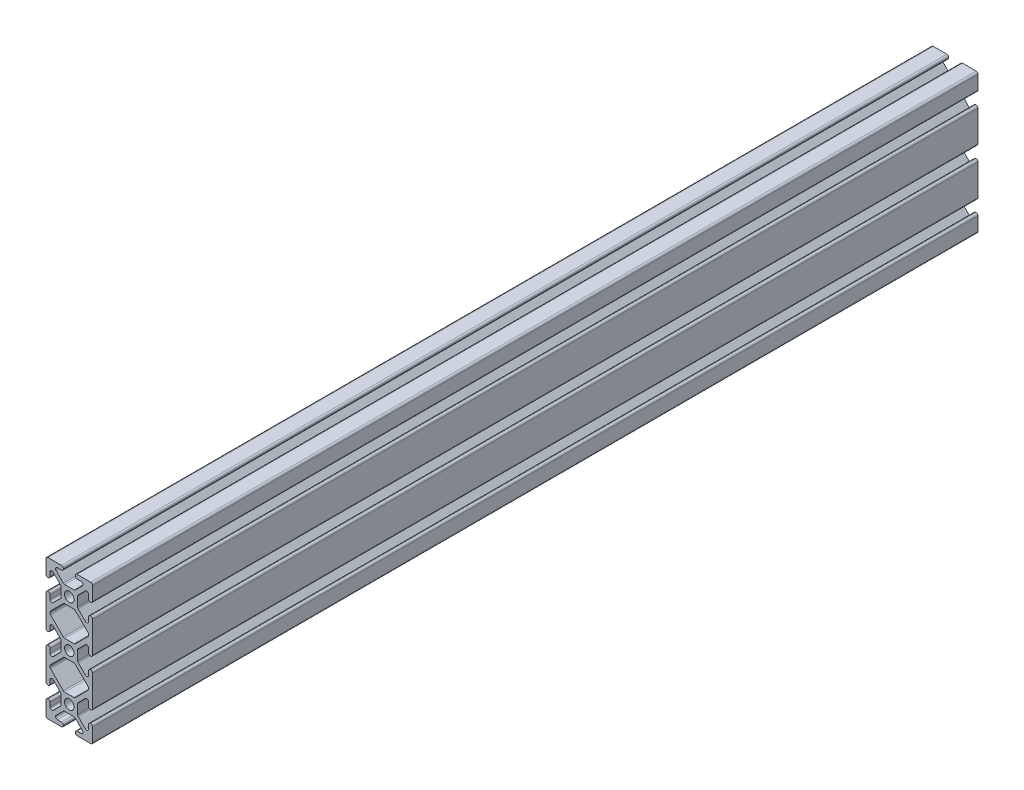
SolidWorks part; units mm, degrees
ref_plane "Front Plane" through (0, 0, 0) normal (0, 0, 1) x (1, 0, 0)
ref_plane "Top Plane" through (0, 0, 0) normal (0, 1, 0) x (1, 0, 0)
ref_plane "Right Plane" through (0, 0, 0) normal (1, 0, 0) x (0, 0, -1)
sketch "Sketch1" plane through (0, 0, 0) normal (0, 0, 1) x (1, 0, 0)
  line L0 (-12.7, 38.1) -> (-12.7, 12.7) construction
  line L1 (-12.7, -38.1) -> (12.7, -38.1) construction
  line L2 (-12.7, 12.7) -> (-12.7, -12.7) construction
  line L3 (-12.7, 38.1) -> (12.7, 38.1) construction
  line L4 (-12.7, -12.7) -> (-12.7, -38.1) construction
  line L5 (-12.7, -38.1) -> (12.7, 38.1) construction
  line L6 (-12.7, 38.1) -> (12.7, -38.1) construction
  line L7 (12.7, 38.1) -> (12.7, 12.7) construction
  line L8 (12.7, 12.7) -> (12.7, -12.7) construction
  line L9 (12.7, -12.7) -> (12.7, -38.1) construction
  line L10 (-12.7, 12.7) -> (12.7, 12.7) construction
  line L11 (-12.7, -12.7) -> (12.7, -12.7) construction
  line L12 (12.7, -12.7) -> (-12.7, -38.1) construction
  line L13 (12.7, -38.1) -> (-12.7, -12.7) construction
  line L14 (0, 38.1) -> (0, -38.1) construction
  line L15 (12.7, 12.7) -> (-12.7, 38.1) construction
  line L16 (12.7, 38.1) -> (-12.7, 12.7) construction
  line L17 (-12.7, 37.084) -> (-12.7, 29.6672)
  line L18 (-11.684, 28.6512) -> (-11.5062, 28.6512)
  line L19 (-10.4902, 29.6672) -> (-10.4902, 31.8748)
  line L20 (-8.7558, 32.5932) -> (-4.8188, 28.6562)
  line L21 (-4.5212, 27.9378) -> (-4.5212, 22.8622)
  line L22 (-4.8188, 22.1438) -> (-8.7558, 18.2068)
  line L23 (-10.4902, 18.9252) -> (-10.4902, 21.1328)
  line L24 (-11.5062, 22.1488) -> (-11.684, 22.1488)
  line L25 (-12.7, 21.1328) -> (-12.7, 4.2672)
  line L26 (-12.7, 0) -> (12.7, 0) construction
  line L27 (-12.7, -25.4) -> (12.7, -25.4) construction
  line L28 (-12.7, 25.4) -> (12.7, 25.4) construction
  line L29 (4.2672, 38.1) -> (11.684, 38.1)
  line L30 (3.2512, 36.9062) -> (3.2512, 37.084)
  line L31 (6.4748, 35.8902) -> (4.2672, 35.8902)
  line L32 (3.2562, 30.2188) -> (7.1932, 34.1558)
  line L33 (-2.5378, 29.9212) -> (2.5378, 29.9212)
  line L34 (-7.1932, 34.1558) -> (-3.2562, 30.2188)
  line L35 (-4.2672, 35.8902) -> (-6.4748, 35.8902)
  line L36 (-3.2512, 37.084) -> (-3.2512, 36.9062)
  line L37 (-11.684, 38.1) -> (-4.2672, 38.1)
  line L38 (4.5212, 2.5378) -> (4.5212, -2.5378)
  line L39 (11.5062, 22.1488) -> (11.684, 22.1488)
  line L40 (10.4902, 18.9252) -> (10.4902, 21.1328)
  line L41 (4.8188, 22.1438) -> (8.7558, 18.2068)
  line L42 (4.5212, 27.9378) -> (4.5212, 22.8622)
  line L43 (8.7558, 32.5932) -> (4.8188, 28.6562)
  line L44 (10.4902, 29.6672) -> (10.4902, 31.8748)
  line L45 (11.684, 28.6512) -> (11.5062, 28.6512)
  line L46 (12.7, 37.084) -> (12.7, 29.6672)
  line L47 (-10.4902, 12.4736) -> (-10.4902, 12.9264)
  line L48 (-10.1926, 13.6448) -> (-3.2562, 20.5812)
  line L49 (-2.5378, 20.8788) -> (2.5378, 20.8788)
  line L50 (10.4902, 12.4736) -> (10.4902, 12.9264)
  line L51 (10.1926, 13.6448) -> (3.2562, 20.5812)
  line L52 (10.1926, 11.7552) -> (3.2562, 4.8188)
  line L53 (-2.5378, 4.5212) -> (2.5378, 4.5212)
  line L54 (-10.1926, 11.7552) -> (-3.2562, 4.8188)
  line L55 (-2.5378, -4.5212) -> (2.5378, -4.5212)
  line L56 (-10.1926, -11.7552) -> (-3.2562, -4.8188)
  line L57 (10.1926, -11.7552) -> (3.2562, -4.8188)
  line L58 (10.4902, -12.4736) -> (10.4902, -12.9264)
  line L59 (10.1926, -13.6448) -> (3.2562, -20.5812)
  line L60 (-2.5378, -20.8788) -> (2.5378, -20.8788)
  line L61 (-10.1926, -13.6448) -> (-3.2562, -20.5812)
  line L62 (-10.4902, -12.4736) -> (-10.4902, -12.9264)
  line L63 (4.8188, -3.2562) -> (8.7558, -7.1932)
  line L64 (11.5062, -22.1488) -> (11.684, -22.1488)
  line L65 (10.4902, -18.9252) -> (10.4902, -21.1328)
  line L66 (4.8188, -22.1438) -> (8.7558, -18.2068)
  line L67 (4.5212, -27.9378) -> (4.5212, -22.8622)
  line L68 (8.7558, -32.5932) -> (4.8188, -28.6562)
  line L69 (10.4902, -29.6672) -> (10.4902, -31.8748)
  line L70 (11.684, -28.6512) -> (11.5062, -28.6512)
  line L71 (12.7, -37.084) -> (12.7, -29.6672)
  line L72 (3.2512, -36.9062) -> (3.2512, -37.084)
  line L73 (6.4748, -35.8902) -> (4.2672, -35.8902)
  line L74 (3.2562, -30.2188) -> (7.1932, -34.1558)
  line L75 (-2.5378, -29.9212) -> (2.5378, -29.9212)
  line L76 (-7.1932, -34.1558) -> (-3.2562, -30.2188)
  line L77 (-4.2672, -35.8902) -> (-6.4748, -35.8902)
  line L78 (-3.2512, -37.084) -> (-3.2512, -36.9062)
  line L79 (-11.684, -38.1) -> (-4.2672, -38.1)
  line L80 (4.2672, -38.1) -> (11.684, -38.1)
  line L81 (4.8188, 3.2562) -> (8.7558, 7.1932)
  line L82 (-11.5062, -22.1488) -> (-11.684, -22.1488)
  line L83 (-10.4902, -18.9252) -> (-10.4902, -21.1328)
  line L84 (-4.8188, -22.1438) -> (-8.7558, -18.2068)
  line L85 (-4.5212, -27.9378) -> (-4.5212, -22.8622)
  line L86 (-8.7558, -32.5932) -> (-4.8188, -28.6562)
  line L87 (-10.4902, -29.6672) -> (-10.4902, -31.8748)
  line L88 (-11.684, -28.6512) -> (-11.5062, -28.6512)
  line L89 (-12.7, -37.084) -> (-12.7, -29.6672)
  line L90 (-4.8188, 3.2562) -> (-8.7558, 7.1932)
  line L91 (-10.4902, 6.4748) -> (-10.4902, 4.2672)
  line L92 (-11.5062, 3.2512) -> (-11.684, 3.2512)
  line L93 (-4.5212, 2.5378) -> (-4.5212, -2.5378)
  line L94 (-12.7, -21.1328) -> (-12.7, -4.2672)
  line L95 (-4.8188, -3.2562) -> (-8.7558, -7.1932)
  line L96 (-10.4902, -6.4748) -> (-10.4902, -4.2672)
  line L97 (-11.5062, -3.2512) -> (-11.684, -3.2512)
  line L98 (10.4902, -6.4748) -> (10.4902, -4.2672)
  line L99 (10.4902, 6.4748) -> (10.4902, 4.2672)
  line L100 (11.5062, 3.2512) -> (11.684, 3.2512)
  line L101 (11.5062, -3.2512) -> (11.684, -3.2512)
  line L102 (12.7, -21.1328) -> (12.7, -4.2672)
  line L103 (12.7, 21.1328) -> (12.7, 4.2672)
  circle A0 centre (0, 25.4) radius 2.6035
  circle A1 centre (0, 0) radius 2.6035
  circle A2 centre (0, -25.4) radius 2.6035
  arc A3 (-12.7, 21.1328) -> (-11.684, 22.1488) centre (-11.684, 21.1328) cw
  arc A4 (-11.5062, 22.1488) -> (-10.4902, 21.1328) centre (-11.5062, 21.1328) cw
  arc A5 (-10.4902, 18.9252) -> (-8.7558, 18.2068) centre (-9.4742, 18.9252) ccw
  arc A6 (-4.8188, 22.1438) -> (-4.5212, 22.8622) centre (-5.5372, 22.8622) ccw
  arc A7 (-4.5212, 27.9378) -> (-4.8188, 28.6562) centre (-5.5372, 27.9378) ccw
  arc A8 (-8.7558, 32.5932) -> (-10.4902, 31.8748) centre (-9.4742, 31.8748) ccw
  arc A9 (-10.4902, 29.6672) -> (-11.5062, 28.6512) centre (-11.5062, 29.6672) cw
  arc A10 (-11.684, 28.6512) -> (-12.7, 29.6672) centre (-11.684, 29.6672) cw
  arc A11 (4.2672, 38.1) -> (3.2512, 37.084) centre (4.2672, 37.084) ccw
  arc A12 (3.2512, 36.9062) -> (4.2672, 35.8902) centre (4.2672, 36.9062) ccw
  arc A13 (6.4748, 35.8902) -> (7.1932, 34.1558) centre (6.4748, 34.8742) cw
  arc A14 (3.2562, 30.2188) -> (2.5378, 29.9212) centre (2.5378, 30.9372) cw
  arc A15 (-2.5378, 29.9212) -> (-3.2562, 30.2188) centre (-2.5378, 30.9372) cw
  arc A16 (-7.1932, 34.1558) -> (-6.4748, 35.8902) centre (-6.4748, 34.8742) cw
  arc A17 (-4.2672, 35.8902) -> (-3.2512, 36.9062) centre (-4.2672, 36.9062) ccw
  arc A18 (-3.2512, 37.084) -> (-4.2672, 38.1) centre (-4.2672, 37.084) ccw
  arc A19 (12.7, 21.1328) -> (11.684, 22.1488) centre (11.684, 21.1328) ccw
  arc A20 (11.5062, 22.1488) -> (10.4902, 21.1328) centre (11.5062, 21.1328) ccw
  arc A21 (10.4902, 18.9252) -> (8.7558, 18.2068) centre (9.4742, 18.9252) cw
  arc A22 (4.8188, 22.1438) -> (4.5212, 22.8622) centre (5.5372, 22.8622) cw
  arc A23 (4.5212, 27.9378) -> (4.8188, 28.6562) centre (5.5372, 27.9378) cw
  arc A24 (8.7558, 32.5932) -> (10.4902, 31.8748) centre (9.4742, 31.8748) cw
  arc A25 (10.4902, 29.6672) -> (11.5062, 28.6512) centre (11.5062, 29.6672) ccw
  arc A26 (11.684, 28.6512) -> (12.7, 29.6672) centre (11.684, 29.6672) ccw
  arc A27 (12.7, 37.084) -> (11.684, 38.1) centre (11.684, 37.084) ccw
  arc A28 (-11.684, 38.1) -> (-12.7, 37.084) centre (-11.684, 37.084) ccw
  arc A29 (-10.1926, 13.6448) -> (-10.4902, 12.9264) centre (-9.4742, 12.9264) ccw
  arc A30 (-2.5378, 20.8788) -> (-3.2562, 20.5812) centre (-2.5378, 19.8628) ccw
  arc A31 (10.1926, 13.6448) -> (10.4902, 12.9264) centre (9.4742, 12.9264) cw
  arc A32 (2.5378, 20.8788) -> (3.2562, 20.5812) centre (2.5378, 19.8628) cw
  arc A33 (10.1926, 11.7552) -> (10.4902, 12.4736) centre (9.4742, 12.4736) ccw
  arc A34 (2.5378, 4.5212) -> (3.2562, 4.8188) centre (2.5378, 5.5372) ccw
  arc A35 (-2.5378, 4.5212) -> (-3.2562, 4.8188) centre (-2.5378, 5.5372) cw
  arc A36 (-10.1926, 11.7552) -> (-10.4902, 12.4736) centre (-9.4742, 12.4736) cw
  arc A37 (2.5378, -4.5212) -> (3.2562, -4.8188) centre (2.5378, -5.5372) cw
  arc A38 (-2.5378, -4.5212) -> (-3.2562, -4.8188) centre (-2.5378, -5.5372) ccw
  arc A39 (10.1926, -11.7552) -> (10.4902, -12.4736) centre (9.4742, -12.4736) cw
  arc A40 (10.1926, -13.6448) -> (10.4902, -12.9264) centre (9.4742, -12.9264) ccw
  arc A41 (2.5378, -20.8788) -> (3.2562, -20.5812) centre (2.5378, -19.8628) ccw
  arc A42 (-2.5378, -20.8788) -> (-3.2562, -20.5812) centre (-2.5378, -19.8628) cw
  arc A43 (-10.1926, -13.6448) -> (-10.4902, -12.9264) centre (-9.4742, -12.9264) cw
  arc A44 (-10.1926, -11.7552) -> (-10.4902, -12.4736) centre (-9.4742, -12.4736) ccw
  arc A45 (12.7, -21.1328) -> (11.684, -22.1488) centre (11.684, -21.1328) cw
  arc A46 (11.5062, -22.1488) -> (10.4902, -21.1328) centre (11.5062, -21.1328) cw
  arc A47 (10.4902, -18.9252) -> (8.7558, -18.2068) centre (9.4742, -18.9252) ccw
  arc A48 (4.8188, -22.1438) -> (4.5212, -22.8622) centre (5.5372, -22.8622) ccw
  arc A49 (4.5212, -27.9378) -> (4.8188, -28.6562) centre (5.5372, -27.9378) ccw
  arc A50 (8.7558, -32.5932) -> (10.4902, -31.8748) centre (9.4742, -31.8748) ccw
  arc A51 (10.4902, -29.6672) -> (11.5062, -28.6512) centre (11.5062, -29.6672) cw
  arc A52 (11.684, -28.6512) -> (12.7, -29.6672) centre (11.684, -29.6672) cw
  arc A53 (4.2672, -38.1) -> (3.2512, -37.084) centre (4.2672, -37.084) cw
  arc A54 (3.2512, -36.9062) -> (4.2672, -35.8902) centre (4.2672, -36.9062) cw
  arc A55 (6.4748, -35.8902) -> (7.1932, -34.1558) centre (6.4748, -34.8742) ccw
  arc A56 (3.2562, -30.2188) -> (2.5378, -29.9212) centre (2.5378, -30.9372) ccw
  arc A57 (-2.5378, -29.9212) -> (-3.2562, -30.2188) centre (-2.5378, -30.9372) ccw
  arc A58 (-7.1932, -34.1558) -> (-6.4748, -35.8902) centre (-6.4748, -34.8742) ccw
  arc A59 (-4.2672, -35.8902) -> (-3.2512, -36.9062) centre (-4.2672, -36.9062) cw
  arc A60 (-3.2512, -37.084) -> (-4.2672, -38.1) centre (-4.2672, -37.084) cw
  arc A61 (12.7, -37.084) -> (11.684, -38.1) centre (11.684, -37.084) cw
  arc A62 (-12.7, -21.1328) -> (-11.684, -22.1488) centre (-11.684, -21.1328) ccw
  arc A63 (-11.5062, -22.1488) -> (-10.4902, -21.1328) centre (-11.5062, -21.1328) ccw
  arc A64 (-10.4902, -18.9252) -> (-8.7558, -18.2068) centre (-9.4742, -18.9252) cw
  arc A65 (-4.8188, -22.1438) -> (-4.5212, -22.8622) centre (-5.5372, -22.8622) cw
  arc A66 (-4.5212, -27.9378) -> (-4.8188, -28.6562) centre (-5.5372, -27.9378) cw
  arc A67 (-8.7558, -32.5932) -> (-10.4902, -31.8748) centre (-9.4742, -31.8748) cw
  arc A68 (-10.4902, -29.6672) -> (-11.5062, -28.6512) centre (-11.5062, -29.6672) ccw
  arc A69 (-11.684, -28.6512) -> (-12.7, -29.6672) centre (-11.684, -29.6672) ccw
  arc A70 (-11.684, -38.1) -> (-12.7, -37.084) centre (-11.684, -37.084) cw
  arc A71 (-4.8188, 3.2562) -> (-4.5212, 2.5378) centre (-5.5372, 2.5378) cw
  arc A72 (-10.4902, 6.4748) -> (-8.7558, 7.1932) centre (-9.4742, 6.4748) cw
  arc A73 (-11.5062, 3.2512) -> (-10.4902, 4.2672) centre (-11.5062, 4.2672) ccw
  arc A74 (-12.7, 4.2672) -> (-11.684, 3.2512) centre (-11.684, 4.2672) ccw
  arc A75 (-4.8188, -3.2562) -> (-4.5212, -2.5378) centre (-5.5372, -2.5378) ccw
  arc A76 (-10.4902, -6.4748) -> (-8.7558, -7.1932) centre (-9.4742, -6.4748) ccw
  arc A77 (-11.5062, -3.2512) -> (-10.4902, -4.2672) centre (-11.5062, -4.2672) cw
  arc A78 (-12.7, -4.2672) -> (-11.684, -3.2512) centre (-11.684, -4.2672) cw
  arc A79 (4.8188, 3.2562) -> (4.5212, 2.5378) centre (5.5372, 2.5378) ccw
  arc A80 (4.8188, -3.2562) -> (4.5212, -2.5378) centre (5.5372, -2.5378) cw
  arc A81 (10.4902, 6.4748) -> (8.7558, 7.1932) centre (9.4742, 6.4748) ccw
  arc A82 (10.4902, -6.4748) -> (8.7558, -7.1932) centre (9.4742, -6.4748) cw
  arc A83 (11.5062, -3.2512) -> (10.4902, -4.2672) centre (11.5062, -4.2672) ccw
  arc A84 (11.5062, 3.2512) -> (10.4902, 4.2672) centre (11.5062, 4.2672) cw
  arc A85 (12.7, -4.2672) -> (11.684, -3.2512) centre (11.684, -4.2672) ccw
  arc A86 (12.7, 4.2672) -> (11.684, 3.2512) centre (11.684, 4.2672) cw
  point P0 (0, 0)
  point P26 (-12.7, 22.1488)
  point P41 (-12.7, 28.6512)
  point P107 (-6.7244, 17.113)
  point P120 (0, 20.8788)
  point P121 (10.4902, 12.7)
  point P132 (-10.4902, 12.7)
  point P249 (-4.5212, 0)
  dimension "D2" = 5.207
  dimension "D8" = 1.016
  dimension "D9" = 3.2512
  dimension "D10" = 1.1049
  dimension "D1" = 25.4
  dimension "D3" = 2.2098
  dimension "D4" = 6.5024
  dimension "D5" = 4.5212
  dimension "D6" = 1.1049
  dimension "D7" = 1.1049
  dimension "D11" = 4.5212
extrude "Main Extrusion" add sketch "Sketch1" along normal mid plane 482.6
sketch "Sketch2" plane through (0, 0, 241.3) normal (0, 0, 1) x (1, 0, 0)
  line L0 (-4.2672, 38.1) -> (-11.684, 38.1) construction
  line L1 (-12.7, -38.1) -> (12.7, -38.1) construction
  line L2 (-12.7, 38.1) -> (-12.7, 12.7) construction
  line L3 (-12.7, 38.1) -> (12.7, 38.1) construction
  line L4 (-12.7, 21.1328) -> (-12.7, 4.2672) construction
  line L5 (-12.7, -38.1) -> (12.7, 38.1) construction
  line L6 (-12.7, 38.1) -> (12.7, -38.1) construction
  line L7 (-12.7, 12.7) -> (-12.7, -12.7) construction
  line L8 (0, 38.1) -> (0, -38.1) construction
  line L9 (-12.7, -4.2672) -> (-12.7, -21.1328) construction
  line L10 (-12.7, -12.7) -> (-12.7, -38.1) construction
  line L11 (12.7, 38.1) -> (12.7, 12.7) construction
  line L12 (12.7, 4.2672) -> (12.7, 21.1328) construction
  line L13 (12.7, 12.7) -> (12.7, -12.7) construction
  line L14 (12.7, -21.1328) -> (12.7, -4.2672) construction
  line L15 (12.7, -12.7) -> (12.7, -38.1) construction
  line L16 (-12.7, 25.4) -> (12.7, 25.4) construction
  line L17 (-12.7, 0) -> (12.7, 0) construction
  line L18 (-12.7, -25.4) -> (12.7, -25.4) construction
  line L19 (-12.7, 12.7) -> (12.7, 12.7) construction
  line L20 (-12.7, -12.7) -> (12.7, -12.7) construction
  line L21 (-3.2512, 36.9062) -> (-3.2512, 37.084) construction
  line L22 (-10.4902, 38.1) -> (-9.4742, 38.1)
  line L23 (-6.477, 38.1) -> (-5.461, 38.1)
  line L24 (-12.7, 38.1) -> (12.7, 12.7) construction
  line L25 (12.7, 12.7) -> (-12.7, -12.7) construction
  line L26 (-12.7, -12.7) -> (12.7, -38.1) construction
  line L27 (-12.7, -38.1) -> (12.7, -12.7) construction
  line L28 (12.7, -12.7) -> (-12.7, 12.7) construction
  line L29 (-12.7, 12.7) -> (12.7, 38.1) construction
  line L30 (6.477, 38.1) -> (5.461, 38.1)
  line L31 (10.4902, 38.1) -> (9.4742, 38.1)
  line L32 (-12.7, 14.9098) -> (-12.7, 15.9258)
  line L33 (-12.7, 18.923) -> (-12.7, 19.939)
  line L34 (-12.7, 31.877) -> (-12.7, 30.861)
  line L35 (-12.7, 35.8902) -> (-12.7, 34.8742)
  line L36 (12.7, 35.8902) -> (12.7, 34.8742)
  line L37 (12.7, 31.877) -> (12.7, 30.861)
  line L38 (12.7, 18.923) -> (12.7, 19.939)
  line L39 (12.7, 14.9098) -> (12.7, 15.9258)
  line L40 (12.7, 10.4902) -> (12.7, 9.4742)
  line L41 (12.7, 6.477) -> (12.7, 5.461)
  line L42 (-12.7, 10.4902) -> (-12.7, 9.4742)
  line L43 (-12.7, 6.477) -> (-12.7, 5.461)
  line L44 (12.7, -6.477) -> (12.7, -5.461)
  line L45 (12.7, -10.4902) -> (12.7, -9.4742)
  line L46 (12.7, -14.9098) -> (12.7, -15.9258)
  line L47 (12.7, -18.923) -> (12.7, -19.939)
  line L48 (12.7, -31.877) -> (12.7, -30.861)
  line L49 (12.7, -35.8902) -> (12.7, -34.8742)
  line L50 (10.4902, -38.1) -> (9.4742, -38.1)
  line L51 (6.477, -38.1) -> (5.461, -38.1)
  line L52 (-6.477, -38.1) -> (-5.461, -38.1)
  line L53 (-10.4902, -38.1) -> (-9.4742, -38.1)
  line L54 (-12.7, -35.8902) -> (-12.7, -34.8742)
  line L55 (-12.7, -31.877) -> (-12.7, -30.861)
  line L56 (-12.7, -18.923) -> (-12.7, -19.939)
  line L57 (-12.7, -14.9098) -> (-12.7, -15.9258)
  line L58 (-12.7, -10.4902) -> (-12.7, -9.4742)
  line L59 (-12.7, -6.477) -> (-12.7, -5.461)
  arc A0 (-10.4902, 38.1) -> (-9.4742, 38.1) centre (-9.9822, 38.1) ccw
  arc A1 (-6.477, 38.1) -> (-5.461, 38.1) centre (-5.969, 38.1) ccw
  arc A2 (6.477, 38.1) -> (5.461, 38.1) centre (5.969, 38.1) cw
  arc A3 (10.4902, 38.1) -> (9.4742, 38.1) centre (9.9822, 38.1) cw
  arc A4 (-12.7, 14.9098) -> (-12.7, 15.9258) centre (-12.7, 15.4178) ccw
  arc A5 (-12.7, 18.923) -> (-12.7, 19.939) centre (-12.7, 19.431) ccw
  arc A6 (-12.7, 31.877) -> (-12.7, 30.861) centre (-12.7, 31.369) cw
  arc A7 (-12.7, 35.8902) -> (-12.7, 34.8742) centre (-12.7, 35.3822) cw
  arc A8 (12.7, 35.8902) -> (12.7, 34.8742) centre (12.7, 35.3822) ccw
  arc A9 (12.7, 31.877) -> (12.7, 30.861) centre (12.7, 31.369) ccw
  arc A10 (12.7, 18.923) -> (12.7, 19.939) centre (12.7, 19.431) cw
  arc A11 (12.7, 14.9098) -> (12.7, 15.9258) centre (12.7, 15.4178) cw
  arc A12 (12.7, 10.4902) -> (12.7, 9.4742) centre (12.7, 9.9822) ccw
  arc A13 (12.7, 6.477) -> (12.7, 5.461) centre (12.7, 5.969) ccw
  arc A14 (-12.7, 10.4902) -> (-12.7, 9.4742) centre (-12.7, 9.9822) cw
  arc A15 (-12.7, 6.477) -> (-12.7, 5.461) centre (-12.7, 5.969) cw
  arc A16 (12.7, -6.477) -> (12.7, -5.461) centre (12.7, -5.969) cw
  arc A17 (12.7, -10.4902) -> (12.7, -9.4742) centre (12.7, -9.9822) cw
  arc A18 (12.7, -14.9098) -> (12.7, -15.9258) centre (12.7, -15.4178) ccw
  arc A19 (12.7, -18.923) -> (12.7, -19.939) centre (12.7, -19.431) ccw
  arc A20 (12.7, -31.877) -> (12.7, -30.861) centre (12.7, -31.369) cw
  arc A21 (12.7, -35.8902) -> (12.7, -34.8742) centre (12.7, -35.3822) cw
  arc A22 (10.4902, -38.1) -> (9.4742, -38.1) centre (9.9822, -38.1) ccw
  arc A23 (6.477, -38.1) -> (5.461, -38.1) centre (5.969, -38.1) ccw
  arc A24 (-6.477, -38.1) -> (-5.461, -38.1) centre (-5.969, -38.1) cw
  arc A25 (-10.4902, -38.1) -> (-9.4742, -38.1) centre (-9.9822, -38.1) cw
  arc A26 (-12.7, -35.8902) -> (-12.7, -34.8742) centre (-12.7, -35.3822) ccw
  arc A27 (-12.7, -31.877) -> (-12.7, -30.861) centre (-12.7, -31.369) ccw
  arc A28 (-12.7, -18.923) -> (-12.7, -19.939) centre (-12.7, -19.431) cw
  arc A29 (-12.7, -14.9098) -> (-12.7, -15.9258) centre (-12.7, -15.4178) cw
  arc A30 (-12.7, -10.4902) -> (-12.7, -9.4742) centre (-12.7, -9.9822) ccw
  arc A31 (-12.7, -6.477) -> (-12.7, -5.461) centre (-12.7, -5.969) ccw
  point P0 (0, 0)
  dimension "D1" = 0.508
  dimension "D2" = 2.2098
  dimension "D3" = 2.2098
